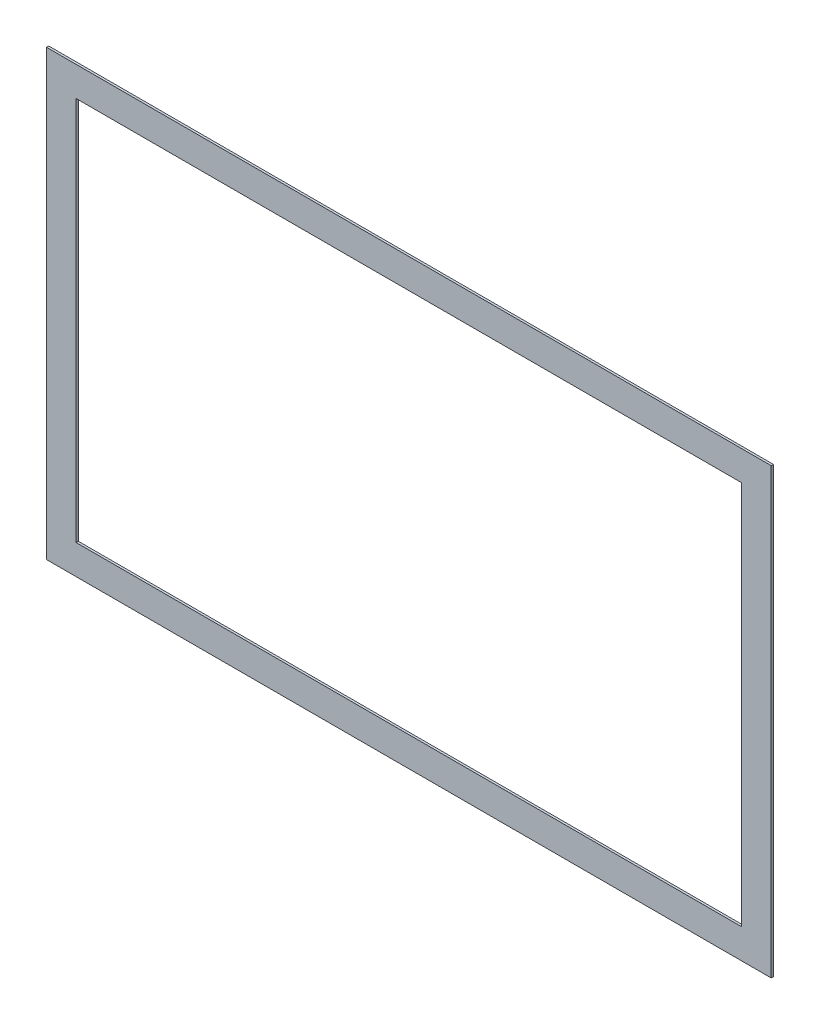
SolidWorks part; units mm, degrees
ref_plane "Front Plane" through (0, 0, 0) normal (0, 0, 1) x (1, 0, 0)
ref_plane "Top Plane" through (0, 0, 0) normal (0, 1, 0) x (1, 0, 0)
ref_plane "Right Plane" through (0, 0, 0) normal (1, 0, 0) x (0, 0, -1)
other "Configuration Table"
sketch "Sketch1" plane through (0, 0, 0) normal (0, 0, 1) x (1, 0, 0)
  line L1 (180, 820) -> (670, 820)
  line L2 (180, 820) -> (180, 1120)
  line L3 (180, 1120) -> (670, 1120)
  line L4 (670, 820) -> (670, 1120)
extrude "OVEN_panel_sprey_1" add sketch "Sketch1" along normal blind 1.5 from offset 38.5 separate body
sketch "Sketch2" plane through (0, 0, 0) normal (0, 0, 1) x (1, 0, 0)
  line L1 (200, 840) -> (650, 840)
  line L2 (200, 840) -> (200, 1100)
  line L3 (200, 1100) -> (650, 1100)
  line L4 (650, 840) -> (650, 1100)
extrude "OVEN_panel_sprey_2" cut sketch "Sketch2" along normal blind 3.5 from offset 37.5
